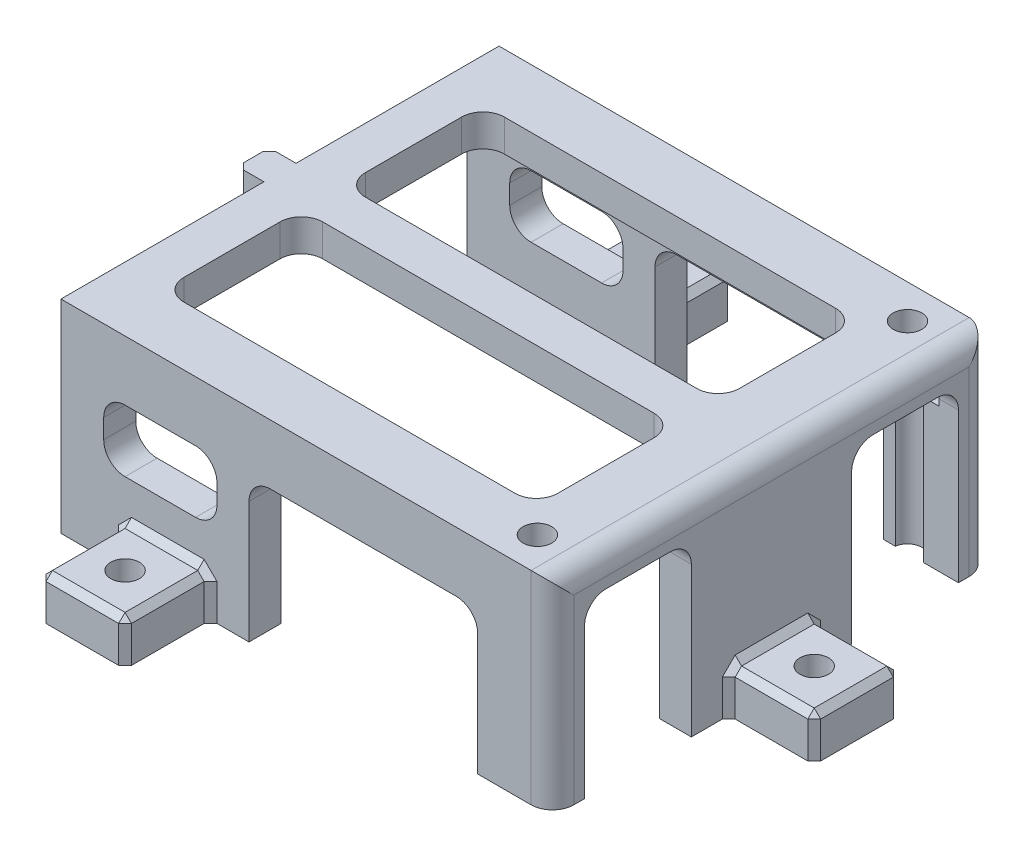
SolidWorks part; units mm, degrees
ref_plane "Front Plane" through (0, 0, 0) normal (0, 0, 1) x (1, 0, 0)
ref_plane "Top Plane" through (0, 0, 0) normal (0, 1, 0) x (1, 0, 0)
ref_plane "Right Plane" through (0, 0, 0) normal (1, 0, 0) x (0, 0, -1)
sketch "Sketch1" plane through (0, 0, 0) normal (0, 1, 0) x (1, 0, 0)
  line L0 (-27.305, 22.225) -> (-27.305, 26.035)
  line L1 (-27.305, -22.225) -> (27.305, -22.225)
  line L3 (-27.305, 22.225) -> (27.305, 22.225)
  line L4 (27.305, -22.225) -> (27.305, 22.225)
  line L5 (-27.305, -22.225) -> (27.305, 22.225) construction
  line L6 (-27.305, 22.225) -> (27.305, -22.225) construction
  line L7 (-27.305, -26.035) -> (31.115, -26.035)
  line L9 (-27.305, 26.035) -> (31.115, 26.035)
  line L10 (31.115, -26.035) -> (31.115, 26.035)
  line L11 (-27.305, -22.847) -> (31.115, 26.035) construction
  line L12 (-27.305, 22.847) -> (31.115, -26.035) construction
  line L13 (-27.305, -22.225) -> (-27.305, -26.035)
  point P0 (0, 0)
  point P6 (0, 0)
  dimension "D1" = 54.61
  dimension "D2" = 58.42
  dimension "D3" = 52.07
  dimension "D4" = 44.45
extrude "Boss-Extrude1" add sketch "Sketch1" along normal blind 20.32
sketch "Sketch2" plane through (0, 20.32, 0) normal (0, 1, 0) x (1, 0, 0)
  line L1 (-27.305, 26.035) -> (31.115, 26.035)
  line L2 (-27.305, 26.035) -> (-27.305, -26.035)
  line L3 (-27.305, -26.035) -> (31.115, -26.035)
  line L4 (31.115, 26.035) -> (31.115, -26.035)
extrude "Boss-Extrude2" add sketch "Sketch2" along normal blind 3.81
sketch "Sketch3" plane through (27.305, 0, 0) normal (-1, 0, 0) x (0, 0, 1)
  line L0 (-22.225, 0) -> (22.225, 0) construction
  line L1 (-22.225, 20.32) -> (-9.525, 20.32)
  line L2 (-22.225, 20.32) -> (-22.225, 0)
  line L3 (-22.225, 0) -> (-9.525, 0)
  line L4 (-9.525, 20.32) -> (-9.525, 0)
  line L6 (22.225, 20.32) -> (9.525, 20.32)
  line L7 (22.225, 20.32) -> (22.225, 0)
  line L8 (22.225, 0) -> (9.525, 0)
  line L9 (9.525, 20.32) -> (9.525, 0)
  dimension "D1" = 12.7
extrude "Cut-Extrude1" cut sketch "Sketch3" against normal up to surface (3.81 mm away) up to face at (31.115, 12.065, 0)
fillet "Fillet2" radius 2.54 3 edges at (31.115, 12.065, -26.035) (31.115, 12.065, 26.035) (31.115, 24.13, 0)
sketch "Sketch4" plane through (31.115, 0, 0) normal (1, 0, 0) x (0, 0, -1)
  line L5 (-9.525, 0) -> (9.525, 0) construction
  line L6 (-5.08, 0) -> (5.08, 0)
  line L7 (-5.08, 0) -> (-5.08, 5.08)
  line L8 (-5.08, 5.08) -> (5.08, 5.08)
  line L9 (5.08, 0) -> (5.08, 5.08)
  line L11 (-9.525, 0) -> (-9.525, 20.32) construction
  point P7 (0, 5.08)
  dimension "D1" = 10.16
  dimension "D2" = 5.08
  dimension "D3" = 9.525
extrude "Boss-Extrude3" add sketch "Sketch4" along normal blind 10.16
chamfer "Chamfer1" distance 0.762 angle 45 8 edges at (31.115, 2.54, -5.08) (31.115, 2.54, 5.08) (36.195, 5.08, -5.08) (41.275, 5.08, 0) (36.195, 5.08, 5.08) (31.115, 5.08, 0) (41.275, 2.54, -5.08) (41.275, 2.54, 5.08)
sketch "Sketch5" plane through (0, 0, 26.035) normal (0, 0, 1) x (1, 0, 0)
  line L0 (-27.305, 0) -> (28.575, 0) construction
  line L1 (-19.685, 0) -> (-9.525, 0)
  line L2 (-19.685, 0) -> (-19.685, 5.08)
  line L3 (-19.685, 5.08) -> (-9.525, 5.08)
  line L4 (-9.525, 0) -> (-9.525, 5.08)
  line L5 (-27.305, 24.13) -> (-27.305, 0) construction
  dimension "D1" = 10.16
  dimension "D2" = 5.08
  dimension "D3" = 7.62
extrude "Boss-Extrude4" add sketch "Sketch5" along normal blind 10.16
chamfer "Chamfer2" distance 0.762 angle 45 8 edges at (-9.525, 2.54, 26.035) (-19.685, 2.54, 26.035) (-9.525, 5.08, 31.115) (-9.525, 2.54, 36.195) (-14.605, 5.08, 36.195) (-14.605, 5.08, 26.035) (-19.685, 5.08, 31.115) (-19.685, 2.54, 36.195)
mirror "Mirror1" about plane through (0, 0, 0) normal (0, 0, 1) of "Chamfer2", "Boss-Extrude4"
hole_wizard "M3 Clearance Hole1" positions "Sketch8" profile "Sketch10" hole size "M3" standard "ANSI Metric" end condition up to next
sketch "Sketch8" plane through (0, 5.08, 0) normal (0, 1, 0) x (1, 0, 0)
  line L0 (-19.685, -35.433) -> (-19.685, -26.797) construction
  line L1 (-10.287, -36.195) -> (-18.923, -36.195) construction
  point P0 (-14.605, -31.115)
  dimension "D1" = 5.08
  dimension "D2" = 5.08
sketch "Sketch10" plane through (-14.605, 5.08, 31.115) normal (1, 0, 0) x (0, 0, 1)
  line L0 (0, 0) -> (0, 5.081)
  line L1 (0, 5.081) -> (1.7, 5.081)
  line L2 (1.7, 5.081) -> (1.7, 0)
  line L5 (1.7, 0) -> (0, 0)
  line L11 (0, -6.35) -> (0, 107.95) construction
  dimension "Thru Hole Dia." = 3.4
  dimension "Thru Hole Depth" = 5.081
mirror "Mirror2" about plane through (0, 0, 0) normal (0, 0, 1) of "M3 Clearance Hole1"
hole_wizard "M3 Clearance Hole2" positions "Sketch11" profile "Sketch12" hole size "M3" standard "ANSI Metric" end condition up to next
sketch "Sketch11" plane through (0, 5.08, 0) normal (0, 1, 0) x (1, 0, 0)
  line L0 (41.275, 4.318) -> (41.275, -4.318) construction
  point P0 (36.195, 0)
  dimension "D1" = 5.08
sketch "Sketch12" plane through (36.195, 5.08, 0) normal (1, 0, 0) x (0, 0, 1)
  line L0 (0, 0) -> (0, 5.08)
  line L1 (0, 5.08) -> (1.7, 5.08)
  line L2 (1.7, 5.08) -> (1.7, 0)
  line L5 (1.7, 0) -> (0, 0)
  line L11 (0, -6.35) -> (0, 107.95) construction
  dimension "Thru Hole Dia." = 3.4
  dimension "Thru Hole Depth" = 5.08
sketch "Sketch13" plane through (0, 24.13, 0) normal (0, 1, 0) x (1, 0, 0)
  line L0 (22.225, -2.54) -> (22.225, -19.05)
  line L1 (22.225, 19.05) -> (-22.225, 19.05)
  line L2 (22.225, 19.05) -> (22.225, 2.54)
  line L3 (22.225, -19.05) -> (-22.225, -19.05)
  line L4 (-22.225, 19.05) -> (-22.225, 2.54)
  line L5 (22.225, 19.05) -> (-22.225, -19.05) construction
  line L6 (22.225, -19.05) -> (-22.225, 19.05) construction
  line L7 (22.225, 2.54) -> (-22.225, 2.54)
  line L9 (22.225, -2.54) -> (-22.225, -2.54)
  line L11 (22.225, 2.54) -> (-22.225, -2.54) construction
  line L12 (22.225, -2.54) -> (-22.225, 2.54) construction
  line L13 (-22.225, -2.54) -> (-22.225, -19.05)
  point P0 (0, 0)
  point P6 (0, 0)
  dimension "D1" = 44.45
  dimension "D2" = 38.1
  dimension "D3" = 5.08
extrude "Cut-Extrude2" cut sketch "Sketch13" against normal up to next
sketch "Sketch14" plane through (0, 0, -26.035) normal (0, 0, -1) x (-1, 0, 0)
  line L0 (-28.575, 0) -> (8.763, 0) construction
  line L1 (-24.123, 0) -> (5.087, 0)
  line L2 (-24.123, 0) -> (-24.123, 19.05)
  line L3 (-24.123, 19.05) -> (4.1472, 19.05)
  line L4 (5.087, 0) -> (5.087, 7.62)
  line L6 (4.1472, 19.05) -> (20.327, 19.05)
  line L8 (5.087, 7.62) -> (20.327, 7.62)
  line L9 (20.327, 19.05) -> (20.327, 7.62)
  point P9 (-24.123, 9.525)
  dimension "D1" = 44.45
  dimension "D2" = 19.05
  dimension "D3" = 11.43
  dimension "D4" = 15.24
sketch "Sketch15" plane through (0, 0, -26.035) normal (0, 0, -1) x (-1, 0, 0)
  line L0 (-28.575, 0) -> (8.763, 0) construction
  line L1 (-22.225, 0) -> (4.953, 0)
  line L2 (-22.225, 0) -> (-22.225, 17.018)
  line L3 (-22.225, 17.018) -> (2.441, 17.018)
  line L4 (4.953, 0) -> (4.953, 9.652)
  line L5 (-28.575, 24.13) -> (-28.575, 0) construction
  line L6 (2.441, 17.018) -> (4.953, 17.018)
  line L8 (8.763, 9.652) -> (22.225, 9.652)
  line L9 (22.225, 17.018) -> (22.225, 9.652)
  line L10 (27.305, 21.59) -> (-28.575, 21.59) construction
  line L11 (8.763, 0) -> (8.763, 4.318) construction
  line L12 (10.287, 5.842) -> (18.923, 5.842) construction
  line L13 (8.763, 17.018) -> (22.225, 17.018)
  line L15 (4.953, 9.652) -> (4.953, 17.018)
  line L17 (8.763, 9.652) -> (8.763, 17.018)
  point P20 (4.953, 13.335)
  dimension "D1" = 6.35
  dimension "D2" = 4.572
  dimension "D3" = 44.45
  dimension "D4" = 3.81
  dimension "D5" = 3.81
  dimension "D6" = 3.81
extrude "Cut-Extrude4" cut sketch "Sketch15" against normal through all
fillet "Fillet3" radius 2.54 24 edges at (-8.763, 9.652, 24.13) (-8.763, 17.018, 24.13) (-22.225, 9.652, 24.13) (-22.225, 17.018, 24.13) (-4.953, 17.018, 24.13) (22.225, 17.018, 24.13) (29.21, 20.32, 9.525) (1.905, 20.32, 22.225) (29.21, 20.32, -9.525) (1.905, 20.32, -22.225) (-8.763, 9.652, -24.13) (-22.225, 9.652, -24.13) (-8.763, 17.018, -24.13) (-22.225, 17.018, -24.13) (-4.953, 17.018, -24.13) (22.225, 17.018, -24.13) (22.225, 22.225, -2.54) (-22.225, 22.225, -19.05) (-22.225, 22.225, -2.54) (22.225, 22.225, -19.05) (22.225, 22.225, 2.54) (-22.225, 22.225, 2.54) (-22.225, 22.225, 19.05) (22.225, 22.225, 19.05)
sketch "Sketch16" plane through (0, 24.13, 0) normal (0, 1, 0) x (1, 0, 0)
  line L0 (-27.305, 26.035) -> (-27.305, -26.035) construction
  line L1 (-24.13, 1.905) -> (-30.48, 1.905)
  line L2 (-24.13, 1.905) -> (-24.13, -1.905)
  line L3 (-24.13, -1.905) -> (-30.48, -1.905)
  line L4 (-30.48, 1.905) -> (-30.48, -1.905)
  line L5 (-24.13, 1.905) -> (-30.48, -1.905) construction
  line L6 (-24.13, -1.905) -> (-30.48, 1.905) construction
  point P0 (-27.305, 0)
  dimension "D1" = 3.81
  dimension "D2" = 6.35
extrude "Boss-Extrude5" add sketch "Sketch16" against normal up to surface (3.81 mm away) up to face at (0, 20.32, 10.795)
chamfer "Chamfer3" distance 0.762 angle 45 5 edges at (-30.48, 22.225, -1.905) (-30.48, 22.225, 1.905) (-28.8925, 20.32, -1.905) (-30.48, 20.32, 0) (-28.8925, 20.32, 1.905)
hole_wizard "M3 Clearance Hole4" positions "Sketch20" profile "Sketch21" hole size "M3" standard "ANSI Metric" end condition through all
sketch "Sketch20" plane through (0, 24.13, 0) normal (0, 1, 0) x (1, 0, 0)
  line L0 (19.685, -2.54) -> (-19.685, -2.54) construction
  point P0 (25.2869, -21.9964)
  point P2 (25.2869, 21.9964)
  dimension "D1" = 19.4564
  dimension "D2" = 43.9928
sketch "Sketch21" plane through (25.2869, 24.13, 21.9964) normal (1, 0, 0) x (0, 0, 1)
  line L0 (0, 0) -> (0, 24.13)
  line L1 (0, 24.13) -> (1.7, 24.13)
  line L2 (1.7, 24.13) -> (1.7, 0)
  line L5 (1.7, 0) -> (0, 0)
  line L11 (0, -6.35) -> (0, 107.95) construction
  dimension "Thru Hole Dia." = 3.4
  dimension "Thru Hole Depth" = 24.13
sketch "Sketch22" plane through (0, 20.32, 0) normal (0, -1, 0) x (1, 0, 0)
  line L1 (28.953, 21.9964) -> (27.12, 25.1714)
  line L2 (27.12, 25.1714) -> (23.4538, 25.1714)
  line L3 (23.4538, 25.1714) -> (21.6207, 21.9964)
  line L4 (21.6207, 21.9964) -> (23.4538, 18.8214)
  line L5 (23.4538, 18.8214) -> (27.12, 18.8214)
  line L6 (27.12, 18.8214) -> (28.953, 21.9964)
  line L7 (28.953, -21.9964) -> (27.12, -18.8214)
  line L8 (27.12, -18.8214) -> (23.4538, -18.8214)
  line L9 (23.4538, -18.8214) -> (21.6207, -21.9964)
  line L10 (21.6207, -21.9964) -> (23.4538, -25.1714)
  line L11 (23.4538, -25.1714) -> (27.12, -25.1714)
  line L12 (27.12, -25.1714) -> (28.953, -21.9964)
  circle A0 centre (25.2869, 21.9964) radius 3.175 construction
  circle A1 centre (25.2869, -21.9964) radius 3.175 construction
  dimension "D1" = 6.35
  dimension "D2" = 6.35
extrude "Cut-Extrude5" cut sketch "Sketch22" along normal blind 3.302
equation "\"variable\"=0.375"
equation "\"D3@Sketch4\"=\"variable\""
